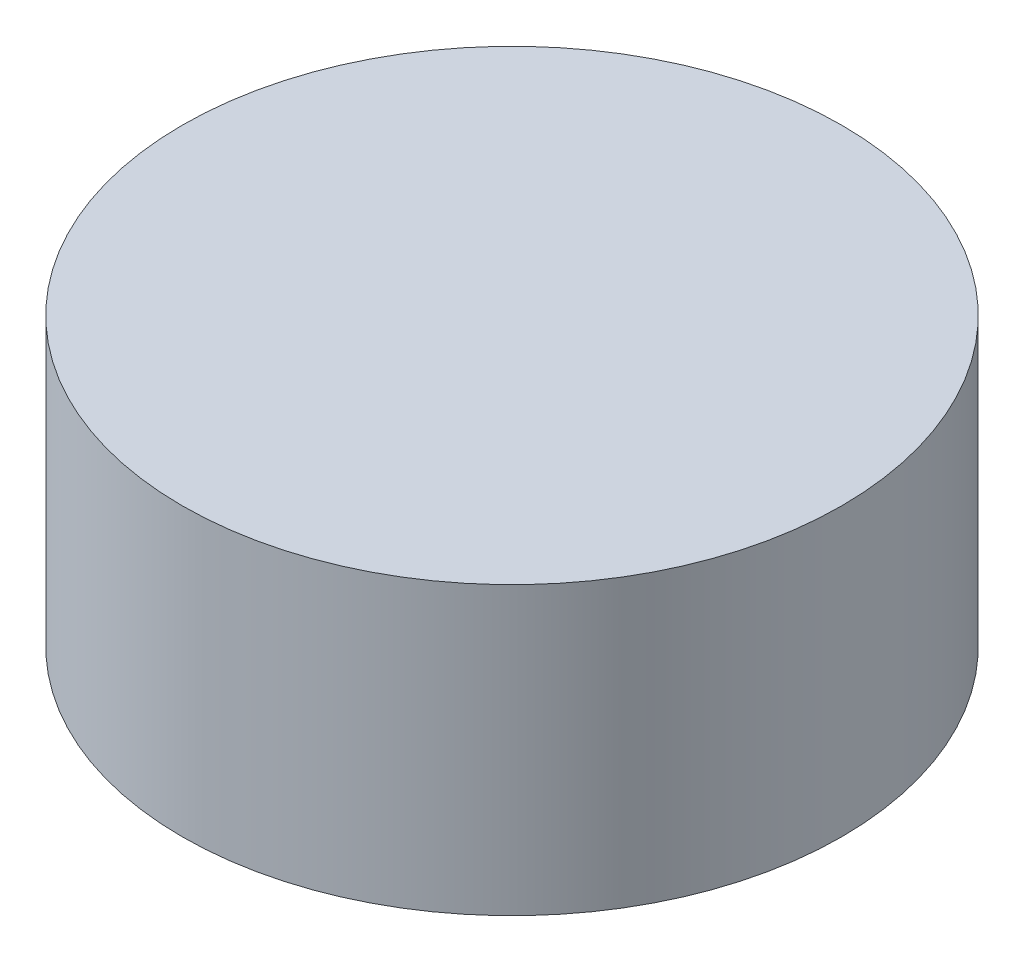
SolidWorks part; units mm, degrees
ref_plane "前视基准面" through (0, 0, 0) normal (0, 0, 1) x (1, 0, 0)
ref_plane "上视基准面" through (0, 0, 0) normal (0, 1, 0) x (1, 0, 0)
ref_plane "右视基准面" through (0, 0, 0) normal (1, 0, 0) x (0, 0, -1)
sketch "草图1" plane through (0, 0, 0) normal (0, 1, 0) x (1, 0, 0)
  circle A0 centre (0, 0) radius 46
  dimension "D1" = 92
extrude "凸台-拉伸1" add sketch "草图1" along normal blind 40
